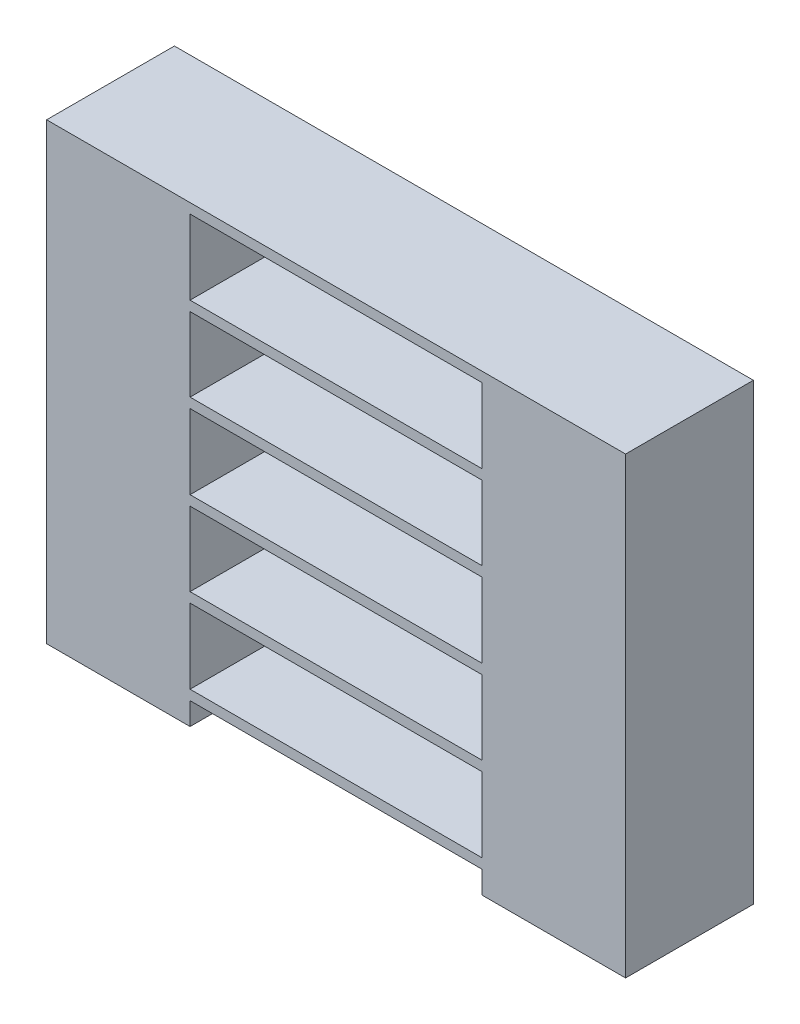
SolidWorks part; units mm, degrees
ref_plane "Front Plane" through (0, 0, 0) normal (0, 0, 1) x (1, 0, 0)
ref_plane "Top Plane" through (0, 0, 0) normal (0, 1, 0) x (1, 0, 0)
ref_plane "Right Plane" through (0, 0, 0) normal (1, 0, 0) x (0, 0, -1)
sketch "Sketch1" plane through (0, 0, 0) normal (1, 0, 0) x (0, 0, -1)
  line L1 (-0.22, 0.87) -> (0.22, 0.87)
  line L2 (-0.22, 0.87) -> (-0.22, -0.87)
  line L3 (-0.22, -0.87) -> (0.22, -0.87)
  line L4 (0.22, 0.87) -> (0.22, -0.87)
  line L5 (-0.22, 0.87) -> (0.22, -0.87) construction
  line L6 (-0.22, -0.87) -> (0.22, 0.87) construction
  point P0 (0, 0)
  dimension "D1" = 0.44
  dimension "D2" = 1.74
extrude "Boss-Extrude1" add sketch "Sketch1" along normal blind 0.03
sketch "Sketch2" plane through (0.03, 0, 0) normal (1, 0, 0) x (0, 0, -1)
  line L0 (-0.22, 0.87) -> (-0.22, -0.87) construction
  line L1 (-0.22, -0.746) -> (0.22, -0.746)
  line L2 (-0.22, -0.746) -> (-0.22, -0.764)
  line L3 (-0.22, -0.764) -> (0.22, -0.764)
  line L4 (0.22, -0.746) -> (0.22, -0.764)
  line L5 (0.22, -0.87) -> (0.22, 0.87) construction
  line L6 (-0.22, -0.87) -> (0.22, -0.87) construction
  line L8 (-0.22, -0.422) -> (0.22, -0.422)
  line L9 (-0.22, -0.422) -> (-0.22, -0.44)
  line L10 (-0.22, -0.44) -> (0.22, -0.44)
  line L11 (0.22, -0.422) -> (0.22, -0.44)
  line L12 (-0.22, -0.1) -> (0.22, -0.1)
  line L13 (-0.22, -0.1) -> (-0.22, -0.118)
  line L14 (-0.22, -0.118) -> (0.22, -0.118)
  line L15 (0.22, -0.1) -> (0.22, -0.118)
  line L16 (-0.22, 0.224) -> (0.22, 0.224)
  line L17 (-0.22, 0.224) -> (-0.22, 0.206)
  line L18 (-0.22, 0.206) -> (0.22, 0.206)
  line L19 (0.22, 0.224) -> (0.22, 0.206)
  line L20 (-0.22, 0.546) -> (0.22, 0.546)
  line L21 (-0.22, 0.546) -> (-0.22, 0.528)
  line L22 (-0.22, 0.528) -> (0.22, 0.528)
  line L23 (0.22, 0.546) -> (0.22, 0.528)
  line L24 (-0.22, 0.87) -> (0.22, 0.87)
  line L25 (-0.22, 0.87) -> (-0.22, 0.852)
  line L26 (-0.22, 0.852) -> (0.22, 0.852)
  line L27 (0.22, 0.87) -> (0.22, 0.852)
  dimension "D1" = 0.106
  dimension "D2" = 0.018
  dimension "D3" = 0.324
  dimension "D4" = 0.322
  dimension "D5" = 0.324
  dimension "D6" = 0.322
  dimension "D7" = 0.324
extrude "Boss-Extrude2" add sketch "Sketch2" along normal blind 1.16
sketch "Sketch3" plane through (1.19, 0, 0) normal (1, 0, 0) x (0, 0, -1)
  line L4 (0.22, -0.87) -> (0.22, 0.87)
  line L5 (-0.22, -0.87) -> (0.22, -0.87)
  line L6 (-0.22, 0.87) -> (-0.22, -0.87)
  line L7 (0.22, 0.87) -> (-0.22, 0.87)
  line L8 (0.22, -0.87) -> (0.22, 0.87)
  line L9 (-0.22, -0.87) -> (0.22, -0.87)
  line L10 (-0.22, 0.87) -> (-0.22, -0.87)
  line L11 (0.22, 0.87) -> (-0.22, 0.87)
  dimension "D1" = 0
extrude "Boss-Extrude3" add sketch "Sketch3" along normal blind 0.03
sketch "Sketch4" plane through (0, 0, -0.22) normal (0, 0, -1) x (-1, 0, 0)
  line L1 (-1.22, 0.87) -> (0, 0.87)
  line L2 (-1.22, 0.87) -> (-1.22, -0.87)
  line L3 (-1.22, -0.87) -> (0, -0.87)
  line L4 (0, 0.87) -> (0, -0.87)
extrude "Boss-Extrude4" add sketch "Sketch4" along normal blind 0.03
sketch "Sketch5" plane through (0, 0, -0.22) normal (0, 0, 1) x (1, 0, 0)
  line L0 (0.03, -0.87) -> (1.19, -0.87) construction
  line L1 (1.19, -0.87) -> (1.19, -0.764) construction
  line L2 (1.19, -0.764) -> (0.03, -0.764) construction
  line L3 (0.03, -0.764) -> (0.03, -0.87) construction
  line L4 (0.03, -0.746) -> (1.19, -0.746) construction
  line L5 (1.19, -0.746) -> (1.19, -0.44) construction
  line L6 (1.19, -0.44) -> (0.03, -0.44) construction
  line L7 (0.03, -0.44) -> (0.03, -0.746) construction
  line L8 (0.03, -0.422) -> (1.19, -0.422) construction
  line L9 (1.19, -0.422) -> (1.19, -0.118) construction
  line L10 (1.19, -0.118) -> (0.03, -0.118) construction
  line L11 (0.03, -0.118) -> (0.03, -0.422) construction
  line L12 (0.03, -0.1) -> (1.19, -0.1) construction
  line L13 (1.19, -0.1) -> (1.19, 0.206) construction
  line L14 (1.19, 0.206) -> (0.03, 0.206) construction
  line L15 (0.03, 0.206) -> (0.03, -0.1) construction
  line L16 (0.03, 0.224) -> (1.19, 0.224) construction
  line L17 (1.19, 0.224) -> (1.19, 0.528) construction
  line L18 (1.19, 0.528) -> (0.03, 0.528) construction
  line L19 (0.03, 0.528) -> (0.03, 0.224) construction
  line L20 (0.03, 0.546) -> (1.19, 0.546) construction
  line L21 (1.19, 0.546) -> (1.19, 0.852) construction
  line L22 (1.19, 0.852) -> (0.03, 0.852) construction
  line L23 (0.03, 0.852) -> (0.03, 0.546) construction
  line L24 (0.03, -0.87) -> (0.05, -0.87)
  line L25 (1.19, -0.87) -> (1.19, -0.764)
  line L26 (1.19, -0.764) -> (0.03, -0.764)
  line L27 (0.03, -0.764) -> (0.03, -0.87)
  line L28 (0.03, -0.746) -> (0.05, -0.746)
  line L29 (1.19, -0.746) -> (1.19, -0.44)
  line L30 (1.19, -0.44) -> (0.03, -0.44)
  line L31 (0.03, -0.44) -> (0.03, -0.746)
  line L32 (0.03, -0.422) -> (0.05, -0.422)
  line L33 (1.19, -0.422) -> (1.19, -0.118)
  line L34 (1.19, -0.118) -> (0.03, -0.118)
  line L35 (0.03, -0.118) -> (0.03, -0.422)
  line L36 (0.03, -0.1) -> (0.05, -0.1)
  line L37 (1.19, -0.1) -> (1.19, 0.206)
  line L38 (1.19, 0.206) -> (0.03, 0.206)
  line L39 (0.03, 0.206) -> (0.03, -0.1)
  line L40 (0.03, 0.224) -> (0.05, 0.224)
  line L41 (1.19, 0.224) -> (1.19, 0.528)
  line L42 (1.19, 0.528) -> (0.03, 0.528)
  line L43 (0.03, 0.528) -> (0.03, 0.224)
  line L44 (0.03, 0.546) -> (0.05, 0.546)
  line L45 (1.19, 0.546) -> (1.19, 0.852)
  line L46 (1.19, 0.852) -> (0.03, 0.852)
  line L47 (0.03, 0.852) -> (0.03, 0.546)
  line L48 (0.05, -0.784) -> (0.05, -0.87)
  line L49 (1.17, -0.784) -> (1.17, -0.87)
  line L50 (1.17, -0.87) -> (1.19, -0.87)
  line L51 (0.05, -0.726) -> (0.05, -0.746)
  line L52 (1.17, -0.726) -> (1.17, -0.746)
  line L53 (0.05, -0.402) -> (0.05, -0.422)
  line L54 (1.17, -0.402) -> (1.17, -0.422)
  line L55 (0.05, -0.08) -> (0.05, -0.1)
  line L56 (0.05, 0.566) -> (1.17, 0.566)
  line L57 (1.17, 0.566) -> (1.17, 0.832)
  line L58 (1.17, 0.832) -> (0.05, 0.832)
  line L59 (0.05, 0.832) -> (0.05, 0.566)
  line L61 (1.17, 0.566) -> (1.17, 0.832)
  line L62 (1.17, 0.832) -> (0.05, 0.832)
  line L63 (0.05, 0.832) -> (0.05, 0.566)
  line L64 (1.17, -0.08) -> (1.17, -0.1)
  line L65 (0.05, 0.244) -> (0.05, 0.224)
  line L66 (1.17, 0.244) -> (1.17, 0.224)
  line L67 (0.05, 0.566) -> (0.05, 0.546)
  line L68 (0.05, 0.244) -> (1.17, 0.244)
  line L69 (1.17, 0.244) -> (1.17, 0.508)
  line L70 (1.17, 0.508) -> (0.05, 0.508)
  line L71 (0.05, 0.508) -> (0.05, 0.244)
  line L73 (1.17, 0.244) -> (1.17, 0.508)
  line L74 (1.17, 0.508) -> (0.05, 0.508)
  line L75 (0.05, 0.508) -> (0.05, 0.244)
  line L76 (1.17, 0.566) -> (1.17, 0.546)
  line L77 (1.17, 0.546) -> (1.19, 0.546)
  line L78 (1.17, 0.224) -> (1.19, 0.224)
  line L79 (1.17, -0.1) -> (1.19, -0.1)
  line L80 (0.05, -0.08) -> (1.17, -0.08)
  line L81 (1.17, -0.08) -> (1.17, 0.186)
  line L82 (1.17, 0.186) -> (0.05, 0.186)
  line L83 (0.05, 0.186) -> (0.05, -0.08)
  line L85 (1.17, -0.08) -> (1.17, 0.186)
  line L86 (1.17, 0.186) -> (0.05, 0.186)
  line L87 (0.05, 0.186) -> (0.05, -0.08)
  line L88 (1.17, -0.422) -> (1.19, -0.422)
  line L89 (1.17, -0.746) -> (1.19, -0.746)
  line L92 (0.05, -0.402) -> (1.17, -0.402)
  line L93 (1.17, -0.402) -> (1.17, -0.138)
  line L94 (1.17, -0.138) -> (0.05, -0.138)
  line L95 (0.05, -0.138) -> (0.05, -0.402)
  line L97 (1.17, -0.402) -> (1.17, -0.138)
  line L98 (1.17, -0.138) -> (0.05, -0.138)
  line L99 (0.05, -0.138) -> (0.05, -0.402)
  line L104 (0.05, -0.726) -> (1.17, -0.726)
  line L105 (1.17, -0.726) -> (1.17, -0.46)
  line L106 (1.17, -0.46) -> (0.05, -0.46)
  line L107 (0.05, -0.46) -> (0.05, -0.726)
  line L109 (1.17, -0.726) -> (1.17, -0.46)
  line L110 (1.17, -0.46) -> (0.05, -0.46)
  line L111 (0.05, -0.46) -> (0.05, -0.726)
  line L116 (0.05, -0.85) -> (1.17, -0.85)
  line L117 (1.17, -0.85) -> (1.17, -0.784)
  line L118 (1.17, -0.784) -> (0.05, -0.784)
  line L119 (0.05, -0.784) -> (0.05, -0.85)
  line L122 (1.17, -0.784) -> (0.05, -0.784)
  dimension "D1" = 0.02
  dimension "D2" = 0.02
  dimension "D3" = 0.02
  dimension "D4" = 0.02
  dimension "D5" = 0.02
  dimension "D6" = 0.02
extrude "Thick in" add sketch "Sketch5" along normal up to surface (0.44 mm away) up to face at (0.61, -0.4085, 0.22)
sketch "Sketch6" plane through (0, 0, 0.22) normal (0, 0, 1) x (1, 0, 0)
  line L0 (1.17, 0.832) -> (0.05, 0.832) construction
  line L1 (0.05, 0.832) -> (0.05, 0.546) construction
  line L3 (1.17, 0.546) -> (1.17, 0.832) construction
  line L4 (1.17, 0.508) -> (0.05, 0.508) construction
  line L5 (0.05, 0.508) -> (0.05, 0.224) construction
  line L7 (1.17, 0.224) -> (1.17, 0.508) construction
  line L8 (0, -0.87) -> (0.05, -0.87)
  line L9 (0.05, -0.87) -> (0.05, -0.784)
  line L10 (0.05, -0.784) -> (1.17, -0.784)
  line L11 (1.17, -0.784) -> (1.17, -0.87)
  line L12 (1.17, -0.87) -> (1.22, -0.87)
  line L13 (1.22, -0.87) -> (1.22, 0.87)
  line L14 (1.22, 0.87) -> (0, 0.87)
  line L15 (0, 0.87) -> (0, -0.87)
  line L16 (0, -0.87) -> (0.05, -0.87)
  line L17 (0.05, -0.87) -> (0.05, -0.784)
  line L18 (0.05, -0.784) -> (1.17, -0.784)
  line L19 (1.17, -0.784) -> (1.17, -0.87)
  line L20 (1.17, -0.87) -> (1.22, -0.87)
  line L21 (1.22, -0.87) -> (1.22, 0.87)
  line L22 (1.22, 0.87) -> (0, 0.87)
  line L23 (0, 0.87) -> (0, -0.87)
  line L24 (1.17, 0.186) -> (0.05, 0.186) construction
  line L25 (0.05, 0.186) -> (0.05, -0.1) construction
  line L27 (1.17, -0.1) -> (1.17, 0.186) construction
  line L28 (1.17, -0.138) -> (0.05, -0.138) construction
  line L29 (0.05, -0.138) -> (0.05, -0.422) construction
  line L31 (1.17, -0.422) -> (1.17, -0.138) construction
  line L32 (1.17, -0.46) -> (0.05, -0.46) construction
  line L33 (0.05, -0.46) -> (0.05, -0.746) construction
  line L35 (1.17, -0.746) -> (1.17, -0.46) construction
  line L36 (1.17, 0.832) -> (0.05, 0.832)
  line L37 (0.05, 0.832) -> (0.05, 0.546)
  line L38 (0.05, 0.546) -> (1.17, 0.546)
  line L39 (1.17, 0.546) -> (1.17, 0.832)
  line L40 (1.17, 0.508) -> (0.05, 0.508)
  line L41 (0.05, 0.508) -> (0.05, 0.224)
  line L42 (0.05, 0.224) -> (1.17, 0.224)
  line L43 (1.17, 0.224) -> (1.17, 0.508)
  line L44 (1.17, 0.186) -> (0.05, 0.186)
  line L45 (0.05, 0.186) -> (0.05, -0.1)
  line L46 (0.05, -0.1) -> (1.17, -0.1)
  line L47 (1.17, -0.1) -> (1.17, 0.186)
  line L48 (1.17, -0.138) -> (0.05, -0.138)
  line L49 (0.05, -0.138) -> (0.05, -0.422)
  line L50 (0.05, -0.422) -> (1.17, -0.422)
  line L51 (1.17, -0.422) -> (1.17, -0.138)
  line L52 (1.17, -0.46) -> (0.05, -0.46)
  line L53 (0.05, -0.46) -> (0.05, -0.746)
  line L54 (0.05, -0.746) -> (1.17, -0.746)
  line L55 (1.17, -0.746) -> (1.17, -0.46)
  dimension "D1" = 0
extrude "Boss-Extrude5" add sketch "Sketch6" along normal blind 0.02
sketch "Sketch7" plane through (1.22, 0, 0) normal (1, 0, 0) x (0, 0, -1)
  line L4 (0.25, 0.87) -> (-0.24, 0.87)
  line L5 (-0.24, 0.87) -> (-0.24, -0.87)
  line L6 (-0.24, -0.87) -> (0.25, -0.87)
  line L9 (-0.24, 0.87) -> (-0.24, -0.87)
  line L10 (-0.24, -0.87) -> (0.25, -0.87)
  line L12 (0.25, 0.87) -> (-0.24, 0.87)
  line L14 (0.25, -0.87) -> (0.25, 0.87)
  line L15 (0.25, -0.87) -> (0.25, 0.87)
  dimension "D1" = 0
extrude "Boss-Extrude6" add sketch "Sketch7" along normal blind 0.5
sketch "Sketch8" plane through (0, 0, 0) normal (-1, 0, 0) x (0, 0, 1)
  line L4 (0.24, 0.87) -> (-0.25, 0.87)
  line L5 (-0.25, 0.87) -> (-0.25, -0.87)
  line L6 (-0.25, -0.87) -> (0.24, -0.87)
  line L7 (0.24, -0.87) -> (0.24, 0.87)
  line L8 (0.24, 0.87) -> (-0.25, 0.87)
  line L9 (-0.25, 0.87) -> (-0.25, -0.87)
  line L10 (-0.25, -0.87) -> (0.24, -0.87)
  line L11 (0.24, -0.87) -> (0.24, 0.87)
  dimension "D1" = 0
extrude "Boss-Extrude7" add sketch "Sketch8" along normal blind 0.5
